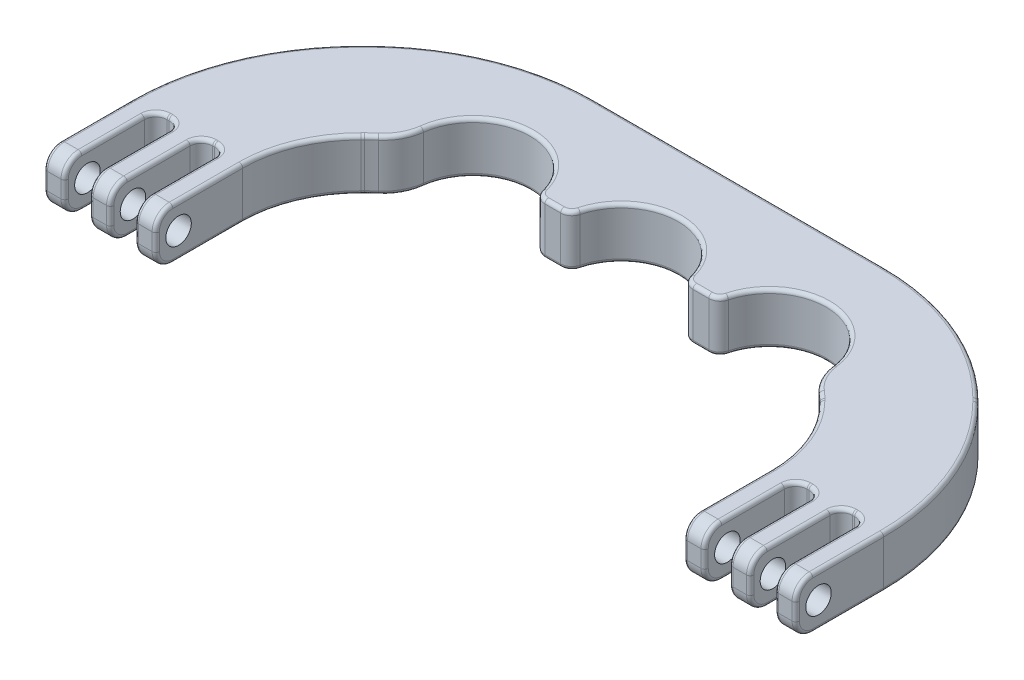
SolidWorks part; units mm, degrees
ref_plane "Front Plane" through (0, 0, 0) normal (0, 0, 1) x (1, 0, 0)
ref_plane "Top Plane" through (0, 0, 0) normal (0, 1, 0) x (1, 0, 0)
ref_plane "Right Plane" through (0, 0, 0) normal (1, 0, 0) x (0, 0, -1)
sketch "Sketch1" plane through (0, 0, 0) normal (0, 1, 0) x (1, 0, 0)
  line L0 (0, 0) -> (52.3875, 0) construction
  line L1 (0, 0) -> (0, 12.7)
  line L2 (2.8956, 0) -> (2.8956, 12.7)
  line L3 (6.35, 0) -> (6.35, 12.7)
  line L4 (9.2456, 0) -> (9.2456, 12.7)
  line L5 (52.3875, 0) -> (52.3875, 50000) construction
  line L6 (12.7, 0) -> (12.7, 12.7)
  line L7 (15.5956, 0) -> (15.5956, 12.7)
  line L8 (0, 0) -> (2.8956, 0)
  line L9 (6.35, 0) -> (9.2456, 0)
  line L10 (12.7, 0) -> (15.5956, 0)
  line L11 (2.8956, 12.7) -> (6.35, 12.7)
  line L12 (9.2456, 12.7) -> (12.7, 12.7)
  line L13 (-947.6125, 44.45) -> (49052.3875, 44.45) construction
  line L14 (15.5956, 12.7) -> (15.5956, 18.9401)
  line L15 (15.5956, 18.9401) -> (25.5099, 28.8544)
  line L16 (25.5099, 28.8544) -> (79.2651, 28.8544)
  line L17 (0, 12.7) -> (0, 25.4)
  line L18 (0, 25.4) -> (19.05, 44.45)
  line L19 (19.05, 44.45) -> (85.725, 44.45)
  line L20 (89.1794, 18.9401) -> (79.2651, 28.8544)
  line L21 (89.1794, 12.7) -> (89.1794, 18.9401)
  line L22 (89.1794, 0) -> (89.1794, 12.7)
  line L23 (92.075, 0) -> (89.1794, 0)
  line L24 (92.075, 0) -> (92.075, 12.7)
  line L25 (95.5294, 12.7) -> (92.075, 12.7)
  line L26 (95.5294, 0) -> (95.5294, 12.7)
  line L27 (98.425, 0) -> (95.5294, 0)
  line L28 (98.425, 0) -> (98.425, 12.7)
  line L29 (101.8794, 12.7) -> (98.425, 12.7)
  line L30 (101.8794, 0) -> (101.8794, 12.7)
  line L31 (104.775, 0) -> (101.8794, 0)
  line L32 (104.775, 0) -> (104.775, 12.7)
  line L33 (104.775, 12.7) -> (104.775, 25.4)
  line L34 (104.775, 25.4) -> (85.725, 44.45)
  point P17 (52.3875, 44.45)
  point P25 (31.7787, 44.0547)
  point P27 (52.3875, 28.8544)
  point P42 (52.3875, 44.45)
  dimension "D1" = 52.3875
  dimension "D2" = 12.7
  dimension "D3" = 6.35
  dimension "D4" = 12.7
  dimension "D5" = 2.8956
  dimension "D6" = 2.8956
  dimension "D7" = 2.8956
  dimension "D8" = 44.45
  dimension "D9" = 15.5956
  dimension "D10" = 135
  dimension "D11" = 15.5956
  dimension "D12" = 19.05
extrude "Profile" add sketch "Sketch1" along normal blind 7.1437
fillet "Profile Fillet I" radius 31.75 4 edges at (104.775, 3.5719, -25.4) (85.725, 3.5719, -44.45) (19.05, 3.5719, -44.45) (0, 3.5719, -25.4)
fillet "Profile Fillet II" radius 16.51 4 edges at (89.1794, 3.5719, -18.9401) (79.2651, 3.5719, -28.8544) (25.5099, 3.5719, -28.8544) (15.5956, 3.5719, -18.9401)
sketch "Sketch2" plane through (0, 0, 0) normal (-1, 0, 0) x (0, 0, 1)
  line L0 (0, 7.1437) -> (0, 0) construction
  circle A0 centre (-3.175, 3.5719) radius 1.778
  point P2 (0, 0)
  point P5 (0, 3.5719)
  dimension "D1" = 3.556
  dimension "D2" = 3.175
extrude "Fastener Holes" cut sketch "Sketch2" against normal through all both and the other way through all
fillet "Attachment Fillets" radius 2.3813 12 edges at (103.3272, 0, 0) (103.3272, 7.1437, 0) (96.9772, 0, 0) (96.9772, 7.1437, 0) (90.6272, 0, 0) (90.6272, 7.1437, 0) (14.1478, 7.1437, 0) (14.1478, 0, 0) (7.7978, 0, 0) (7.7978, 7.1437, 0) (1.4478, 0, 0) (1.4478, 7.1437, 0)
fillet "Attachment Fillets II" radius 1.5875 8 edges at (101.8794, 3.5719, -12.7) (98.425, 3.5719, -12.7) (95.5294, 3.5719, -12.7) (92.075, 3.5719, -12.7) (12.7, 3.5719, -12.7) (9.2456, 3.5719, -12.7) (6.35, 3.5719, -12.7) (2.8956, 3.5719, -12.7)
sketch "Sketch3" plane through (0, 7.1437, 0) normal (0, 1, 0) x (1, 0, 0)
  line L1 (52.3875, 41.5544) -> (52.3875, 50041.5544) construction
  line L2 (32.3486, 28.8544) -> (72.4264, 28.8544) construction
  circle A3 centre (52.3875, 28.0606) radius 7.9375
  circle A4 centre (73.025, 28.0606) radius 7.9375
  circle A5 centre (31.75, 28.0606) radius 7.9375
  point P4 (52.3875, 28.8544)
  point P9 (0, 0)
  point P10 (70.2159, 40.7606)
  dimension "D1" = 15.875
  dimension "D3" = 20.6375
  dimension "D2" = 0.7937
extrude "Gripping Feature" cut sketch "Sketch3" against normal through all
fillet "Gripping Feature Fillet I" radius 1.5875 4 edges at (65.1273, 3.5719, -28.8544) (60.2852, 3.5719, -28.8544) (44.4898, 3.5719, -28.8544) (39.6477, 3.5719, -28.8544)
fillet "Gripping Feature Fillet II" radius 6.35 2 edges at (80.8197, 3.5719, -26.5618) (23.9553, 3.5719, -26.5618)
fillet "Fillet9" radius 0.508 132 edges at (98.425, 6.4463, -0.6975) (98.425, 3.5719, 0) (98.425, 0.6975, -0.6975) (98.425, 0, -6.7469) (98.89, 0, -12.235) (100.1522, 0, -12.7) (101.4144, 0, -12.235) (101.8794, 0, -6.7469) (101.8794, 0.6975, -0.6975) (101.8794, 3.5719, 0) (101.8794, 6.4463, -0.6975) (101.8794, 7.1437, -6.7469) (101.4144, 7.1437, -12.235) (100.1522, 7.1437, -12.7) (98.89, 7.1437, -12.235) (92.075, 6.4463, -0.6975) (92.075, 3.5719, 0) (92.075, 0.6975, -0.6975) (92.075, 0, -6.7469) (92.54, 0, -12.235) (93.8022, 0, -12.7) (95.0644, 0, -12.235) (95.5294, 0, -6.7469) (95.5294, 0.6975, -0.6975) (95.5294, 3.5719, 0) (95.5294, 6.4463, -0.6975) (95.5294, 7.1437, -6.7469) (95.0644, 7.1437, -12.235) (93.8022, 7.1437, -12.7) (92.54, 7.1437, -12.235) (12.235, 7.1437, -12.235) (10.9728, 7.1437, -12.7) (9.7106, 7.1437, -12.235) (9.2456, 7.1437, -6.7469) (9.2456, 6.4463, -0.6975) (9.2456, 3.5719, 0) (9.2456, 0.6975, -0.6975) (9.2456, 0, -6.7469) (9.7106, 0, -12.235) (10.9728, 0, -12.7) (12.235, 0, -12.235) (12.7, 0, -6.7469) (12.7, 0.6975, -0.6975) (12.7, 3.5719, 0) (12.7, 6.4463, -0.6975) (5.885, 7.1437, -12.235) (4.6228, 7.1437, -12.7) (3.3606, 7.1437, -12.235) (2.8956, 7.1437, -6.7469) (2.8956, 6.4463, -0.6975) (2.8956, 3.5719, 0) (2.8956, 0.6975, -0.6975) (2.8956, 0, -6.7469) (3.3606, 0, -12.235) (4.6228, 0, -12.7) (5.885, 0, -12.235) (6.35, 0, -6.7469) (6.35, 0.6975, -0.6975) (6.35, 3.5719, 0) (6.35, 6.4463, -0.6975) (15.5956, 7.1437, -7.2413) (15.5956, 6.4463, -0.6975) (15.5956, 3.5719, 0) (15.5956, 0.6975, -0.6975) (15.5956, 0, -7.2413) (16.8523, 0, -18.4195) (20.5528, 0, -23.8972) (21.164, 0, -24.4888) (23.1568, 0, -26.77) (31.2269, 0, -35.9809) (40.0004, 0, -29.1869) (42.0688, 0, -28.8544) (44.1371, 0, -29.1869) (52.3875, 0, -35.9981) (60.6379, 0, -29.1869) (62.7062, 0, -28.8544) (64.7746, 0, -29.1869) (73.5481, 0, -35.9809) (81.6182, 0, -26.77) (83.611, 0, -24.4888) (84.2222, 0, -23.8972) (87.9227, 0, -18.4195) (89.1794, 0, -7.2413) (89.1794, 0.6975, -0.6975) (89.1794, 3.5719, 0) (89.1794, 6.4463, -0.6975) (89.1794, 7.1437, -7.2413) (87.9227, 7.1437, -18.4195) (84.2222, 7.1437, -23.8972) (83.611, 7.1437, -24.4888) (81.6182, 7.1437, -26.77) (73.5481, 7.1437, -35.9809) (64.7746, 7.1437, -29.1869) (62.7062, 7.1437, -28.8544) (60.6379, 7.1437, -29.1869) (52.3875, 7.1437, -35.9981) (44.1371, 7.1437, -29.1869) (42.0688, 7.1437, -28.8544) (40.0004, 7.1437, -29.1869) (31.2269, 7.1437, -35.9809) (23.1568, 7.1437, -26.77) (21.164, 7.1437, -24.4888) (20.5528, 7.1437, -23.8972) (9.525, 7.1437, -34.925) (20.0511, 7.1437, -42.0332) (52.3875, 7.1437, -44.45) (84.7239, 7.1437, -42.0332) (95.25, 7.1437, -34.925) (102.3582, 7.1437, -24.3989) (104.775, 7.1437, -7.315) (104.775, 6.4463, -0.6975) (104.775, 3.5719, 0) (104.775, 0.6975, -0.6975) (104.775, 0, -7.315) (102.3582, 0, -24.3989) (95.25, 0, -34.925) (84.7239, 0, -42.0332) (52.3875, 0, -44.45) (20.0511, 0, -42.0332) (9.525, 0, -34.925) (2.4168, 0, -24.3989) (0, 0, -7.315) (0, 0.6975, -0.6975) (0, 3.5719, 0) (0, 6.4463, -0.6975) (0, 7.1437, -7.315) (98.425, 7.1437, -6.7469) (92.075, 7.1437, -6.7469) (12.7, 7.1437, -6.7469) (6.35, 7.1437, -6.7469) (16.8523, 7.1437, -18.4195) (2.4168, 7.1437, -24.3989)
